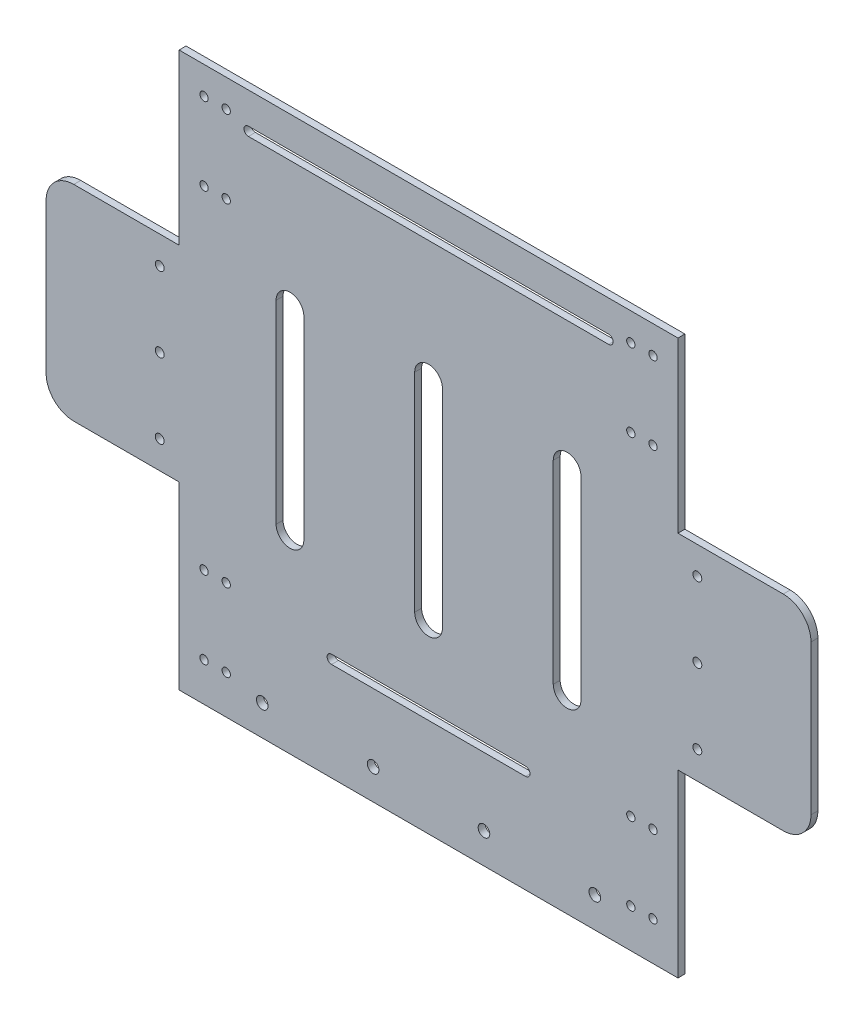
SolidWorks part; units mm, degrees
ref_plane "前视基准面" through (0, 0, 0) normal (0, 0, 1) x (1, 0, 0)
ref_plane "上视基准面" through (0, 0, 0) normal (0, 1, 0) x (1, 0, 0)
ref_plane "右视基准面" through (0, 0, 0) normal (1, 0, 0) x (0, 0, -1)
other "Configuration Table"
sketch "草图1" plane through (0, 0, 0) normal (0, 0, 1) x (1, 0, 0)
  line L0 (-90, -35) -> (-90, -100)
  line L1 (-90, 100) -> (90, 100)
  line L2 (-90, 100) -> (-90, 39)
  line L3 (-90, -100) -> (90, -100)
  line L4 (90, 100) -> (90, 39)
  line L5 (0, -100) -> (0, 100) construction
  line L6 (90, -35) -> (90, -100)
  line L7 (-90, 39) -> (-138, 39)
  line L9 (-90, -35) -> (-138, -35)
  line L10 (-138, 39) -> (-138, -35)
  line L11 (90, 39) -> (138, 39)
  line L13 (90, -35) -> (138, -35)
  line L14 (138, 39) -> (138, -35)
  point P0 (0, 0)
  dimension "D1" = 180
  dimension "D2" = 200
  dimension "D3" = 61
  dimension "D4" = 65
  dimension "D5" = 48
  dimension "D6" = 48
extrude "凸台-拉伸1" add sketch "草图1" along normal blind 2.5
sketch "草图4" plane through (0, 0, 2.5) normal (0, 0, 1) x (1, 0, 0)
  line L0 (-50, 39.3062) -> (-50, -30.6938) construction
  line L1 (-45, 39.3062) -> (-45, -30.6938)
  line L2 (-55, 39.3062) -> (-55, -30.6938)
  line L3 (0, 41.8062) -> (0, -33.1938) construction
  line L4 (5, 41.8062) -> (5, -33.1938)
  line L5 (-5, 41.8062) -> (-5, -33.1938)
  line L6 (50, 39.3062) -> (50, -30.6938) construction
  line L7 (55, 39.3062) -> (55, -30.6938)
  line L8 (45, 39.3062) -> (45, -30.6938)
  line L9 (-138, 39) -> (-138, -35) construction
  arc A0 (-45, 39.3062) -> (-55, 39.3062) centre (-50, 39.3062) ccw
  arc A1 (-55, -30.6938) -> (-45, -30.6938) centre (-50, -30.6938) ccw
  arc A2 (5, 41.8062) -> (-5, 41.8062) centre (0, 41.8062) ccw
  arc A3 (-5, -33.1938) -> (5, -33.1938) centre (0, -33.1938) ccw
  arc A4 (55, 39.3062) -> (45, 39.3062) centre (50, 39.3062) ccw
  arc A5 (45, -30.6938) -> (55, -30.6938) centre (50, -30.6938) ccw
  point P2 (-50, 4.3062)
  point P7 (0, 4.3062)
  point P15 (50, 4.3062)
  dimension "D1" = 88
  dimension "D2" = 10
  dimension "D3" = 10
  dimension "D4" = 10
  dimension "D5" = 50
  dimension "D6" = 75
  dimension "D7" = 70
  dimension "D8" = 70
extrude "切除-拉伸1" cut sketch "草图4" against normal through all
fillet "圆角1" radius 10 1 edges at (-138, 39, 1.25)
fillet "圆角2" radius 10 1 edges at (-138, -35, 1.25)
fillet "圆角3" radius 10 1 edges at (138, -35, 1.25)
fillet "圆角4" radius 10 1 edges at (138, 39, 1.25)
sketch "草图5" plane through (0, 0, 0) normal (0, 0, -1) x (-1, 0, 0)
  circle A0 centre (-60, -89) radius 2.1
  circle A1 centre (-20, -89) radius 2.1
  circle A2 centre (20, -89) radius 2.1
  circle A3 centre (60, -89) radius 2.1
extrude "切除-拉伸2" cut sketch "草图5" against normal through all
sketch "草图6" plane through (0, 0, 2.5) normal (0, 0, 1) x (1, 0, 0)
  circle A0 centre (-81, 90) radius 1.5
  circle A1 centre (-73, 90) radius 1.5
  circle A2 centre (-81, 62) radius 1.5
  circle A3 centre (-73, 62) radius 1.5
  circle A4 centre (73, 90) radius 1.5
  circle A5 centre (81, 90) radius 1.5
  circle A6 centre (73, 62) radius 1.5
  circle A7 centre (81, 62) radius 1.5
  circle A8 centre (-81, -58) radius 1.5
  circle A9 centre (-73, -58) radius 1.5
  circle A10 centre (-81, -86) radius 1.5
  circle A11 centre (-73, -86) radius 1.5
  circle A12 centre (73, -58) radius 1.5
  circle A13 centre (81, -58) radius 1.5
  circle A14 centre (73, -86) radius 1.5
  circle A15 centre (81, -86) radius 1.5
  dimension "D1" = 3
  dimension "D2" = 3
  dimension "D3" = 3
  dimension "D4" = 3
extrude "切除-拉伸3" cut sketch "草图6" against normal through all
sketch "草图7" plane through (0, 0, 2.5) normal (0, 0, 1) x (1, 0, 0)
  circle A0 centre (-97, 29) radius 1.6
  circle A1 centre (-97, 2) radius 1.6
  circle A2 centre (-97, -25) radius 1.6
  circle A3 centre (97, 29) radius 1.6
  circle A4 centre (97, 2) radius 1.6
  circle A5 centre (97, -25) radius 1.6
extrude "切除-拉伸4" cut sketch "草图7" against normal through all
sketch "草图8" plane through (0, 0, 2.5) normal (0, 0, 1) x (1, 0, 0)
  line L0 (-35, -62.9) -> (35, -62.9) construction
  line L1 (-35, -61.3) -> (35, -61.3)
  line L2 (-35, -64.5) -> (35, -64.5)
  line L3 (-35, -61.3) -> (35, -61.3) construction
  arc A0 (-35, -61.3) -> (-35, -64.5) centre (-35, -62.9) ccw
  arc A1 (35, -64.5) -> (35, -61.3) centre (35, -62.9) ccw
  point P2 (0, -62.9)
extrude "切除-拉伸5" cut sketch "草图8" against normal through all
sketch "草图9" plane through (0, 0, 2.5) normal (0, 0, 1) x (1, 0, 0)
  line L21 (65, 88.7) -> (-65, 88.7)
  line L22 (-65, 85.5) -> (65, 85.5)
  line L23 (65, 88.7) -> (-65, 88.7)
  line L24 (-65, 85.5) -> (65, 85.5)
  arc A22 (65, 85.5) -> (65, 88.7) centre (65, 87.1) ccw
  arc A23 (-65, 88.7) -> (-65, 85.5) centre (-65, 87.1) ccw
  arc A24 (65, 85.5) -> (65, 88.7) centre (65, 87.1) ccw
  arc A25 (-65, 88.7) -> (-65, 85.5) centre (-65, 87.1) ccw
  dimension "D1" = 0
extrude "切除-拉伸6" cut sketch "草图9" against normal through all
